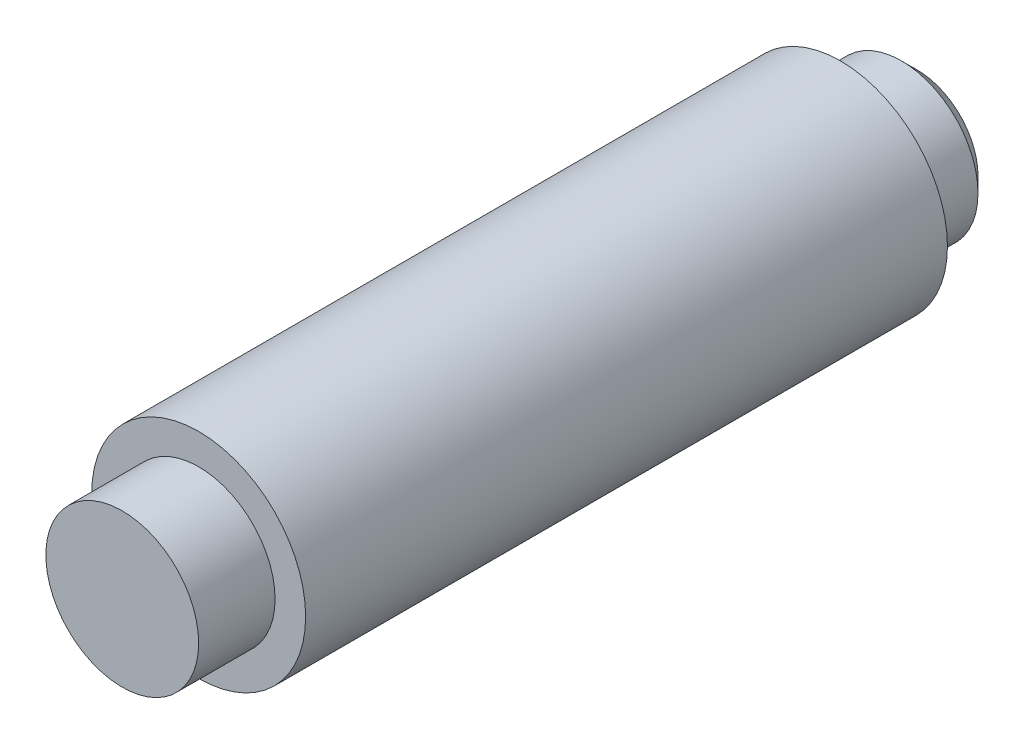
SolidWorks part; units mm, degrees
ref_plane "Front Plane" through (0, 0, 0) normal (0, 0, 1) x (1, 0, 0)
ref_plane "Top Plane" through (0, 0, 0) normal (0, 1, 0) x (1, 0, 0)
ref_plane "Right Plane" through (0, 0, 0) normal (1, 0, 0) x (0, 0, -1)
sketch "Sketch2" plane through (0, 0, 0) normal (0, 0, 1) x (1, 0, 0)
  circle A0 centre (0, 0) radius 1.25
  dimension "D1" = 2.5
sketch "Sketch3" plane through (0, 0, 0) normal (0, 0, 1) x (1, 0, 0)
  line L5 (-3.5, 3.5) -> (3.5, 3.5) construction
  line L6 (-3.5, 3.5) -> (-3.5, -3.5) construction
  line L7 (-3.5, -3.5) -> (3.5, -3.5) construction
  line L8 (3.5, 3.5) -> (3.5, -3.5) construction
  circle A0 centre (0, 0) radius 3.5
  point P4 (0, 3.5)
  point P6 (-3.5, 0)
  dimension "D1" = 7
extrude "Boss-Extrude1" add sketch "Sketch3" along normal blind 21
sketch "Sketch4" plane through (0, 0, 0) normal (0, 0, 1) x (1, 0, 0)
  circle A0 centre (0, 0) radius 2.5
  dimension "D1" = 5
extrude "Boss-Extrude2" add sketch "Sketch4" against normal blind 2.5
sketch "Sketch5" plane through (0, 0, 21) normal (0, 0, 1) x (1, 0, 0)
  circle A0 centre (0, 0) radius 2.5
  dimension "D1" = 5
extrude "Boss-Extrude3" add sketch "Sketch5" along normal blind 2.5
chamfer "Chamfer1" distance 0.5 angle 45 1 edges at (2.5, 0, -2.5)
equation "\"length\"=21"
equation "\"D1@Boss-Extrude1\"=\"length\""
